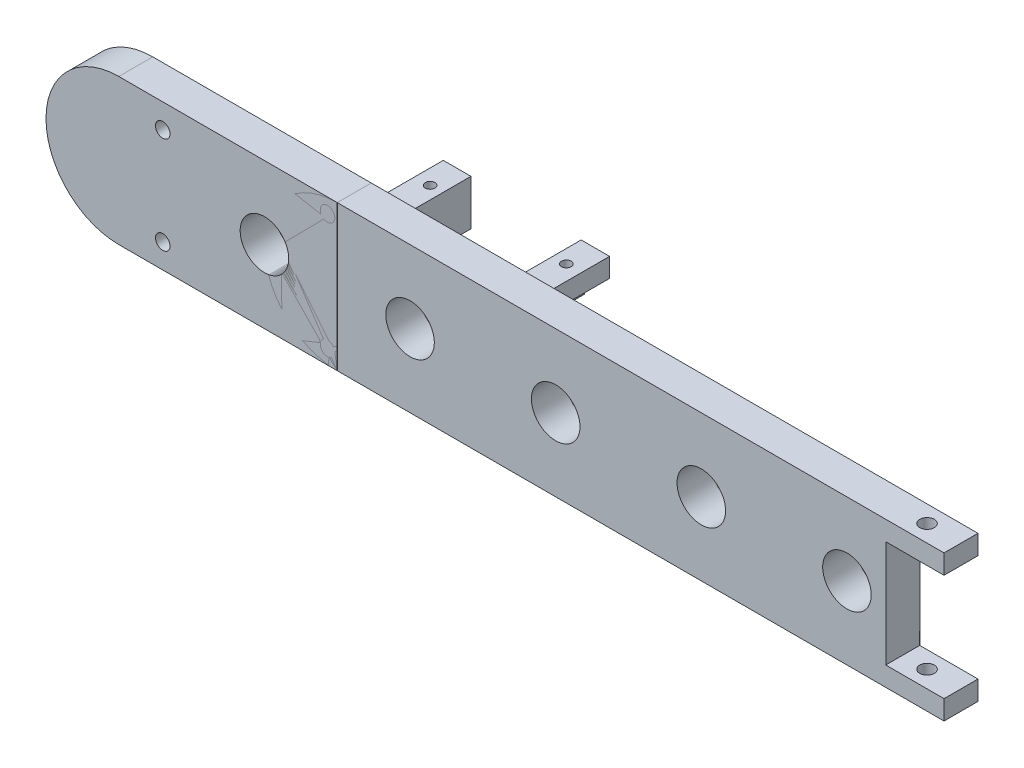
SolidWorks part; units mm, degrees
ref_plane "Front Plane" through (0, 0, 0) normal (0, 0, 1) x (1, 0, 0)
ref_plane "Top Plane" through (0, 0, 0) normal (0, 1, 0) x (1, 0, 0)
ref_plane "Right Plane" through (0, 0, 0) normal (1, 0, 0) x (0, 0, -1)
sketch "Sketch1" plane through (0, 0, 0) normal (0, 0, 1) x (1, 0, 0)
  line L0 (-200, 0) -> (50, 0)
  line L1 (50, -30) -> (-200, -30)
  arc A0 (50, 0) -> (50, -30) centre (50, -15) cw
  arc A1 (-200, -30) -> (-200, 0) centre (-200, -15) cw
  point P7 (-75, 0)
  dimension "D3" = 50
  dimension "D1" = 125
  dimension "D2" = 30
extrude "Boss-Extrude1" add sketch "Sketch1" along normal blind 7
sketch "Sketch2" plane through (0, 0, 7) normal (0, 0, 1) x (1, 0, 0)
  line L2 (50, 0) -> (-200, 0) construction
  circle A0 centre (-185, -15) radius 5
  arc A6 (-200, 0) -> (-200, -30) centre (-200, -15) ccw construction
  point P22 (-215, -15)
  dimension "D1" = 10
  dimension "D3" = 15
  dimension "D2" = 30
extrude "Cut-Extrude1" cut sketch "Sketch2" against normal blind 7
sketch "Sketch5" plane through (0, 0, 0) normal (0, 1, 0) x (1, 0, 0)
  line L1 (-318.748, 64.8797) -> (45.4135, 64.8797) construction
  line L2 (-318.748, 64.8797) -> (-318.748, -30.5338) construction
  line L3 (-318.748, -30.5338) -> (45.4135, -30.5338) construction
  line L4 (45.4135, 64.8797) -> (45.4135, -30.5338) construction
  line L5 (-318.748, 64.8797) -> (45.4135, -30.5338) construction
  line L6 (-318.748, -30.5338) -> (45.4135, 64.8797) construction
  point P0 (-136.6672, 17.1729)
pattern_linear "LPattern1" count 7 spacing 30 along (1, 0, 0) of "Cut-Extrude1"
sketch "Sketch6" plane through (0, 0, 0) normal (0, 0, -1) x (-1, 0, 0)
  circle A0 centre (-50, -15) radius 5
  dimension "D1" = 10
extrude "Cut-Extrude2" cut sketch "Sketch6" against normal blind 10
sketch "Sketch7" plane through (0, 0, 0) normal (1, 0, 0) x (0, 0, -1)
  line L0 (20.1244, -8.0466) -> (20.1244, -21.3918)
  line L1 (0, -8.0466) -> (0, -21.3918)
  line L2 (0, -30) -> (0, 0) construction
  arc A0 (20.1244, -21.3918) -> (0, -21.3918) centre (10.0622, -13.1301) cw
  arc A1 (20.1244, -8.0466) -> (0, -8.0466) centre (10.0622, -15.3827) ccw
  dimension "D3" = 12.4526
  dimension "D4" = 13.0194
  dimension "D1" = 13.3452
  dimension "D2" = 20.1244
extrude "Boss-Extrude2" add sketch "Sketch7" along normal blind 21
sketch "Sketch8" plane through (21, 0, 0) normal (1, 0, 0) x (0, 0, -1)
  line L0 (0.3437, -8.6037) -> (0.3437, -21.0037)
  line L1 (0.3437, -21.0037) -> (3.2516, -23.3301)
  line L2 (3.2516, -23.3301) -> (6.1148, -24.6722)
  line L3 (6.1148, -24.6722) -> (10.1412, -25.388)
  line L4 (10.1412, -25.388) -> (14.1229, -24.6722)
  line L5 (14.1229, -24.6722) -> (17.1651, -23.3301)
  line L6 (17.1651, -23.3301) -> (19.6704, -20.9533)
  line L7 (19.6704, -20.9533) -> (19.6704, -8.5533)
  arc A0 (0.3437, -8.6037) -> (19.6704, -8.5533) centre (10.0259, -15.8054) cw
  dimension "D1" = 12.4
extrude "Cut-Extrude3" cut sketch "Sketch8" against normal blind 21
sketch "Sketch9" plane through (0, 0, 0) normal (0, 0, -1) x (-1, 0, 0)
  line L0 (-50, -15) -> (-29.5, -15)
  line L1 (-29.5, -6.25) -> (-29.5, -23.75)
  circle A0 centre (-29.5, -6.25) radius 1.5
  circle A1 centre (-29.5, -23.75) radius 1.5
  point P6 (-29.5, -15)
  dimension "D3" = 3
  dimension "D4" = 3
  dimension "D1" = 20.5
  dimension "D2" = 17.5
extrude "Cut-Extrude4" cut sketch "Sketch9" against normal up to next contours A1 | A0
sketch "Sketch10" plane through (0, 0, -20.1244) normal (0, 0, -1) x (-1, 0, 0)
  line L0 (-21, -26.1494) -> (0, -26.1494) construction
  line L1 (0, -2.9301) -> (-5.2715, -2.9301)
  line L2 (0, -2.9301) -> (0, -26.1494)
  line L3 (0, -26.1494) -> (-5.2715, -26.1494)
  line L4 (-5.2715, -2.9301) -> (-5.2715, -26.1494)
  dimension "D1" = 5.2715
extrude "Cut-Extrude5" cut sketch "Sketch10" against normal up to surface (20.1244 mm away) up to face at (28, -23.75, 0)
sketch "Sketch11" plane through (0, 0, 0) normal (0, 0, -1) x (-1, 0, 0)
  line L0 (60.0976, -6.42) -> (60.0976, -23.9134)
  line L1 (60.0976, -23.9134) -> (36.2199, -23.9134)
  line L2 (36.2199, -23.9134) -> (36.2199, -6.6133)
  line L3 (36.2199, -6.6133) -> (31.0205, -6.6133)
  line L4 (31.0205, -6.6133) -> (31.0205, -2.6749)
  line L5 (31.0205, -2.6749) -> (65.2766, -2.6749)
  line L6 (65.2766, -2.6749) -> (65.2766, -6.42)
  line L7 (65.2766, -6.42) -> (60.0976, -6.42)
  line L8 (200, -30) -> (-50, -30) construction
  line L9 (-50, 0) -> (200, 0) construction
  line L10 (-5.2715, -21.3918) -> (-5.2715, -8.0466) construction
  line L11 (-5.2715, -21.0037) -> (-5.2715, -8.6037) construction
  line L12 (193.9754, -6.286) -> (193.9754, -16.5408)
  line L13 (193.9754, -16.5408) -> (170.0976, -16.5408)
  line L14 (170.0976, -16.5408) -> (170.0976, -6.4792)
  line L15 (170.0976, -6.4792) -> (164.8982, -6.4792)
  line L16 (164.8982, -6.4792) -> (164.8982, -2.5408)
  line L17 (164.8982, -2.5408) -> (199.1543, -2.5408)
  line L18 (199.1543, -2.5408) -> (199.1543, -6.286)
  line L19 (199.1543, -6.286) -> (193.9754, -6.286)
  circle A0 centre (65, -15) radius 5 construction
  point P26 (65.2766, -4.5474)
  dimension "D1" = 34.2561
  dimension "D2" = 6.0866
  dimension "D3" = 2.6749
  dimension "D4" = 41.4915
  dimension "D5" = 4.9024
  dimension "D6" = 3.7451
  dimension "D7" = 3.9384
  dimension "D8" = 36.292
  dimension "D9" = 34.2561
  dimension "D10" = 3.7451
  dimension "D11" = 110
  dimension "D12" = 2.5408
  dimension "D13" = 23.8777
  dimension "D14" = 14
  dimension "D15" = 99.6216
  dimension "D16" = 6.4792
extrude "Boss-Extrude3" add sketch "Sketch11" along normal blind 14
sketch "Sketch12" plane through (0, -2.6749, 0) normal (0, 1, 0) x (1, 0, 0)
  line L0 (-65.2766, 14) -> (-65.2766, 0) construction
  line L1 (-59.5766, 12.8538) -> (-36.8766, 12.8538)
  line L2 (-59.5766, 12.8538) -> (-59.5766, 0.5538)
  line L3 (-59.5766, 0.5538) -> (-36.8766, 0.5538)
  line L4 (-36.8766, 12.8538) -> (-36.8766, 0.5538)
  line L5 (-193.4543, 14.9752) -> (-170.7543, 14.9752)
  line L6 (-193.4543, 14.9752) -> (-193.4543, 0.2731)
  line L7 (-193.4543, 0.2731) -> (-170.7543, 0.2731)
  line L8 (-170.7543, 14.9752) -> (-170.7543, 0.2731)
  line L9 (-199.1543, 14) -> (-199.1543, 0) construction
  line L10 (-61.9264, 21.0679) -> (-39.5264, 21.0679)
  line L11 (-61.9264, 21.0679) -> (-61.9264, 33.1679)
  line L12 (-61.9264, 33.1679) -> (-39.5264, 33.1679)
  line L13 (-39.5264, 21.0679) -> (-39.5264, 33.1679)
  dimension "D1" = 5.7
  dimension "D2" = 5.7
  dimension "D3" = 12.1
  dimension "D4" = 22.4
  dimension "D5" = 12.3
  dimension "D6" = 22.7
  dimension "D7" = 22.7
extrude "Cut-Extrude6" cut sketch "Sketch12" against normal blind 22 and the other way blind 1 contours L4 L1 L2 L3 | L8 L5 L6 L7
sketch "Sketch13" plane through (0, -2.6749, 0) normal (0, 1, 0) x (1, 0, 0)
  line L0 (-199.1543, 14) -> (-199.1543, 0) construction
  line L1 (-199.1543, 14) -> (-193.4543, 14) construction
  line L2 (-61.1766, 7.0028) -> (-61.1766, 2.942) construction
  line L3 (-65.2766, 14) -> (-65.2766, 0) construction
  line L4 (-35.1205, 8.19) -> (-35.1205, 7.609) construction
  line L5 (-35.1205, 7.609) -> (-35.1205, 2.942) construction
  line L6 (-31.0205, 14) -> (-31.0205, 0) construction
  line L7 (-65.2766, 14) -> (-31.0205, 14) construction
  line L8 (-195.0543, 8.5238) -> (-195.0543, 4.463) construction
  line L9 (-164.8982, 14) -> (-164.8982, 0) construction
  line L10 (-168.9982, 8.19) -> (-168.9982, 7.609) construction
  line L11 (-168.9982, 7.609) -> (-168.9982, 2.942) construction
  circle A0 centre (-62.1766, 8.19) radius 1
  circle A1 centre (-34.1205, 8.19) radius 1
  circle A2 centre (-196.0543, 8.19) radius 1
  circle A3 centre (-167.9982, 8.19) radius 1
  point P28 (-199.1543, 7)
  dimension "D1" = 2
  dimension "D2" = 2
  dimension "D4" = 4.1
  dimension "D8" = 2
  dimension "D9" = 2
  dimension "D3" = 5.81
  dimension "D5" = 4.1
  dimension "D6" = 4.1
  dimension "D7" = 5.81
  dimension "D10" = 4.1
extrude "Cut-Extrude7" cut sketch "Sketch13" against normal blind 7 and the other way blind 7 contours A3 | A2 | A0 | A1
sketch "Sketch14" plane through (-36.2199, 0, 0) normal (1, 0, 0) x (0, 0, -1)
  line L0 (14, -6.6133) -> (14, -23.9134) construction
  line L1 (14, -11.9134) -> (2, -11.9134)
  line L2 (14, -11.9134) -> (14, -23.9134)
  line L3 (14, -23.9134) -> (2, -23.9134)
  line L4 (2, -11.9134) -> (2, -23.9134)
  line L5 (14, -23.9134) -> (0, -23.9134) construction
  dimension "D1" = 0
  dimension "D2" = 12
  dimension "D3" = 12
  dimension "D4" = 0
extrude "Cut-Extrude8" cut sketch "Sketch14" against normal up to surface (157.7554 mm away) up to face at (-193.9754, -11.4134, -7)
sketch "Sketch16" plane through (0, 0, 0) normal (0, 0, -1) x (-1, 0, 0)
  line L1 (-65, 22.8789) -> (75, 22.8789)
  line L2 (-65, 22.8789) -> (-65, -48.8787)
  line L3 (-65, -48.8787) -> (75, -48.8787)
  line L4 (75, 22.8789) -> (75, -48.8787)
  dimension "D1" = 140
extrude "Cut-Extrude10" cut sketch "Sketch16" against normal up to next and the other way blind 24
sketch "Sketch17" plane through (-75, 0, 0) normal (1, 0, 0) x (0, 0, -1)
  line L0 (-7, 0) -> (-7, -30) construction
  line L1 (-7, -4) -> (0, -4)
  line L2 (-7, -4) -> (-7, -26)
  line L3 (-7, -26) -> (0, -26)
  line L4 (0, -4) -> (0, -26)
  line L5 (0, 0) -> (0, -30) construction
  line L6 (-7, -30) -> (0, -30) construction
  line L7 (0, 0) -> (-7, 0) construction
  dimension "D1" = 4
  dimension "D2" = 4
extrude "Cut-Extrude11" cut sketch "Sketch17" against normal blind 12 contours L1 L4 L3 L2
sketch "Sketch18" plane through (0, 0, 0) normal (0, 1, 0) x (1, 0, 0)
  line L0 (-75, 0) -> (-75, -7) construction
  line L1 (-75, -7) -> (-200, -7) construction
  circle A0 centre (-82, -3.5) radius 1.5
  dimension "D1" = 3
  dimension "D2" = 7
  dimension "D3" = 3.5
extrude "Cut-Extrude12" cut sketch "Sketch18" against normal through all
sketch "Sketch19" plane through (0, 0, 7) normal (0, 0, 1) x (1, 0, 0)
  line L0 (-75, 0) -> (-200, 0) construction
  line L1 (-200, -30) -> (-75, -30) construction
  circle A0 centre (-202, -3) radius 1.5
  circle A1 centre (-202, -27) radius 1.5
  arc A2 (-200, 0) -> (-200, -30) centre (-200, -15) ccw construction
  point P8 (-215, -15)
  dimension "D1" = 3
  dimension "D2" = 13
  dimension "D3" = 3
  dimension "D4" = 3
extrude "Cut-Extrude13" cut sketch "Sketch19" against normal through all
sketch "Sketch20" plane through (0, 0, 7) normal (0, 0, 1) x (1, 0, 0)
  line L1 (-200, 0) -> (-245, 0)
  line L2 (-200, 0) -> (-200, -30)
  line L3 (-200, -30) -> (-245, -30)
  line L4 (-245, 0) -> (-245, -30)
  arc A0 (-245, 0) -> (-245, -30) centre (-245, -15) ccw
  circle M5 centre (-202, -3) radius 1.5
  circle M6 centre (-202, -27) radius 1.5
  arc M14 (-200, 0) -> (-200, -30) centre (-200, -15) ccw
  dimension "D2" = 15
  dimension "D1" = 45
extrude "Boss-Extrude4" add sketch "Sketch20" against normal blind 7 separate body contours L1 L4 L3 M14 | L4 A0 | M6 | L2 M14 M6 M5 | M5
sketch "Sketch21" plane through (0, 0, 7) normal (0, 0, 1) x (1, 0, 0)
  line L0 (-235.95, 0) -> (-235.95, -30)
  line L1 (-200, -30) -> (-245, -30) construction
  circle A0 centre (-235.95, -25) radius 1.5
  circle A1 centre (-235.95, -5) radius 1.5
  arc A2 (-245, 0) -> (-245, -30) centre (-245, -15) ccw construction
  point P2 (-235.95, -30)
  point P8 (0, 0)
  point P10 (-179.9438, 22.8367)
  point P13 (-260, -15)
  dimension "D5" = 3
  dimension "D6" = 3
  dimension "D1" = 5
  dimension "D2" = 30
  dimension "D3" = 20
  dimension "D4" = 24.05
extrude "Cut-Extrude14" cut sketch "Sketch21" against normal blind 10 contours A0 | A1
sketch "Sketch22" plane through (0, 0, 7) normal (0, 0, 1) x (1, 0, 0)
  line L0 (-200, -30) -> (-245, -30) construction
  circle A0 centre (-215, -15) radius 5
  arc A1 (-245, 0) -> (-245, -30) centre (-245, -15) ccw construction
  dimension "D1" = 10
  dimension "D2" = 30
  dimension "D3" = 15
extrude "Cut-Extrude15" cut sketch "Sketch22" against normal through all both and the other way through all
